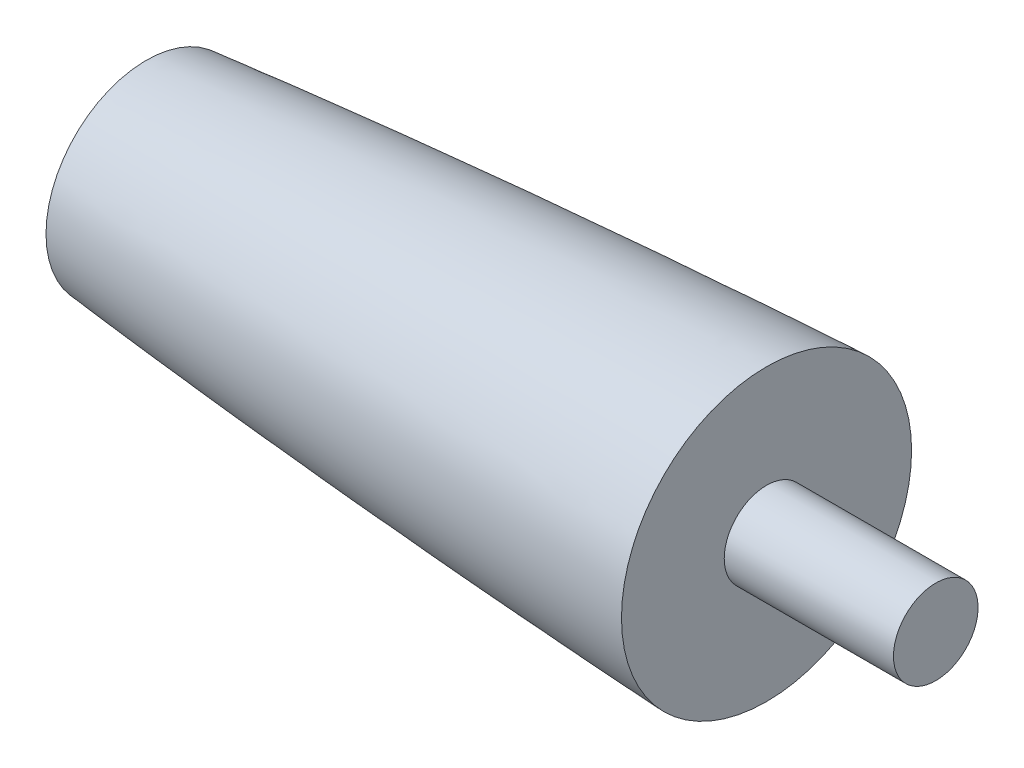
SolidWorks part; units mm, degrees
ref_plane "Front Plane" through (0, 0, 0) normal (0, 0, 1) x (1, 0, 0)
ref_plane "Top Plane" through (0, 0, 0) normal (0, 1, 0) x (1, 0, 0)
ref_plane "Right Plane" through (0, 0, 0) normal (1, 0, 0) x (0, 0, -1)
sketch "Sketch1" plane through (0, 0, 0) normal (0, 1, 0) x (1, 0, 0)
  line L0 (186.2, 30.0883) -> (186.2, 0)
  line L1 (186.2, 0) -> (423.2, 0)
  line L2 (423.2, 0) -> (423.2, 12.7)
  line L3 (423.2, 12.7) -> (372.4, 12.7)
  line L4 (372.4, 12.7) -> (372.4, 43.5413)
  spline S0 degree 4 poles (167.7526, 28.2003) (168.0659, 28.2332) (168.6708, 28.2969) (169.6836, 28.4045) (171.7184, 28.6158) (173.2895, 28.7814) (176.8672, 29.1476) (179.1701, 29.386) (184.5301, 29.9229) (186.7852, 30.147) (191.9193, 30.6511) (196.1251, 31.0563) (201.8419, 31.6) (207.895, 32.1611) (214.2071, 32.7356) (220.3703, 33.2832) (226.6243, 33.8281) (232.8251, 34.356) (239.0597, 34.8759) (245.2753, 35.3827) (251.5037, 35.8798) (259.13, 36.475) (268.3205, 37.1718) (279.0618, 37.9569) (289.8162, 38.7082) (299.1527, 39.3359) (306.9528, 39.8438) (313.162, 40.239) (319.4345, 40.6277) (325.597, 41.0016) (331.9466, 41.3754) (337.9869, 41.7248) (344.5393, 42.0901) (350.249, 42.4051) (357.3501, 42.7791) (362.1487, 43.0316) (370.219, 43.4347) (373.379, 43.59) (379.8399, 43.9008) (383.201, 44.0568) (387.1054, 44.2375) (389.1954, 44.3313) (390.4621, 44.3887) (391.0241, 44.4137) knots 0 0 0 0 0 0.005205 0.010409 0.020819 0.031228 0.041637 0.062204 0.08277 0.096715 0.11066 0.138549 0.166438 0.194328 0.222217 0.250107 0.277996 0.305886 0.333775 0.361665 0.389554 0.417444 0.470505 0.526284 0.582063 0.609953 0.637842 0.665732 0.693621 0.721511 0.7494 0.77729 0.805179 0.833069 0.860958 0.888848 0.916737 0.937553 0.958369 0.979184 0.989592 1 1 1 1 1 construction
  spline S1 degree 4 poles (186.2, 30.0883) (186.8477, 30.1525) (188.1682, 30.2828) (191.9193, 30.6511) (196.1251, 31.0563) (201.8419, 31.6) (207.895, 32.1611) (214.2071, 32.7356) (220.3703, 33.2832) (226.6243, 33.8281) (232.8251, 34.356) (239.0597, 34.8759) (245.2753, 35.3827) (251.5037, 35.8798) (259.13, 36.475) (268.3205, 37.1718) (279.0618, 37.9569) (289.8162, 38.7082) (299.1527, 39.3359) (306.9528, 39.8438) (313.162, 40.239) (319.4345, 40.6277) (325.597, 41.0016) (331.9466, 41.3754) (337.9869, 41.7248) (344.5393, 42.0901) (350.249, 42.4051) (357.3501, 42.7791) (362.1487, 43.0316) (368.6112, 43.3544) (371.0998, 43.4777) (372.4, 43.5413) knots 0.08277 0.08277 0.08277 0.08277 0.08277 0.096715 0.11066 0.138549 0.166438 0.194328 0.222217 0.250107 0.277996 0.305886 0.333775 0.361665 0.389554 0.417444 0.470505 0.526284 0.582063 0.609953 0.637842 0.665732 0.693621 0.721511 0.7494 0.77729 0.805179 0.833069 0.860958 0.888848 0.916737 0.916737 0.916737 0.916737 0.916737
revolve "Revolve1" add sketch "Sketch1" angle 360 about L1
sketch "Sketch2" plane through (186.2, 0, 0) normal (-1, 0, 0) x (0, 0, 1)
  circle A0 centre (0, 0) radius 12.7
extrude "Cut-Extrude1" cut sketch "Sketch2" against normal blind 50.8
